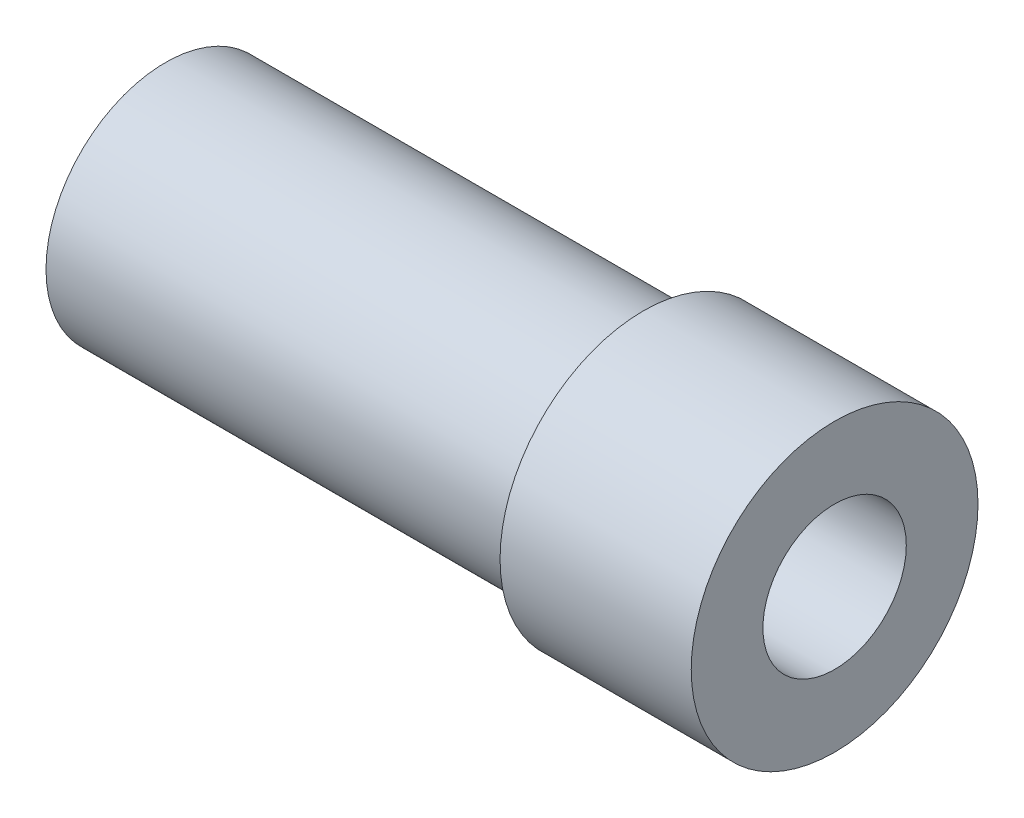
SolidWorks part; units mm, degrees
ref_plane "Front Plane" through (0, 0, 0) normal (1, 0, 0) x (0, 1, 0)
ref_plane "Top Plane" through (0, 0, 0) normal (0, 0, 1) x (0, 1, 0)
ref_plane "Right Plane" through (0, 0, 0) normal (0, 1, 0) x (-1, 0, 0)
sketch "Sketch2" plane through (0, 0, 0) normal (1, 0, 0) x (0, 1, 0)
  circle A0 centre (0, 0) radius 7.9375
  circle A1 centre (0, 0) radius 4.7625
  dimension "D1" = 15.875
  dimension "D2" = 9.525
extrude "Boss-Extrude1" add sketch "Sketch2" along normal blind 44.45
sketch "Sketch3" plane through (44.45, 0, 0) normal (1, 0, 0) x (0, 1, 0)
  circle A0 centre (0, 0) radius 7.9375
  circle A1 centre (0, 0) radius 9.525
  dimension "D1" = 19.05
  dimension "D2" = 15.875
extrude "Boss-Extrude2" add sketch "Sketch3" against normal blind 12.7
